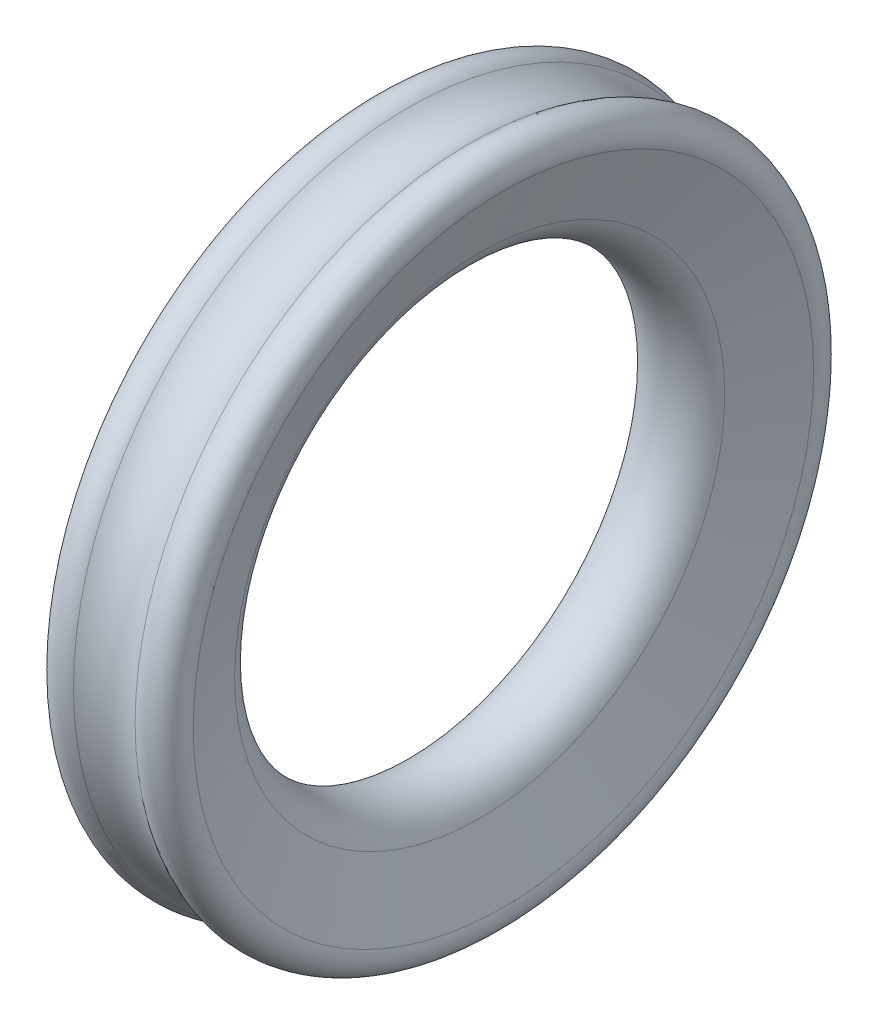
SolidWorks part; units mm, degrees
ref_plane "Front Plane" through (0, 0, 0) normal (0, 0, 1) x (1, 0, 0)
ref_plane "Top Plane" through (0, 0, 0) normal (0, 1, 0) x (1, 0, 0)
ref_plane "Right Plane" through (0, 0, 0) normal (1, 0, 0) x (0, 0, -1)
sketch "Sketch2" plane through (0, 0, 0) normal (0, 0, 1) x (1, 0, 0)
  line L0 (0, 0) -> (0, 36) construction
  line L1 (0, 0) -> (10.273, 0) construction
  line L2 (5.6382, 33.9479) -> (8.9234, 42.9739)
  line L3 (-5.6382, 33.9479) -> (-8.9234, 42.9739)
  arc A0 (-5.6382, 33.9479) -> (5.6382, 33.9479) centre (0, 36) ccw
  arc A1 (8.9234, 42.9739) -> (4.273, 46.3762) centre (6.1043, 44) ccw
  arc A2 (-8.9234, 42.9739) -> (-4.273, 46.3762) centre (-6.1043, 44) cw
  arc A3 (-4.273, 46.3762) -> (4.273, 46.3762) centre (0, 51.9207) ccw
  dimension "D1" = 6
  dimension "D3" = 3
  dimension "D5" = 7
  dimension "D2" = 30
  dimension "D4" = 40
  dimension "D6" = 47
revolve "Revolve1" add sketch "Sketch2" angle 360 about L1
